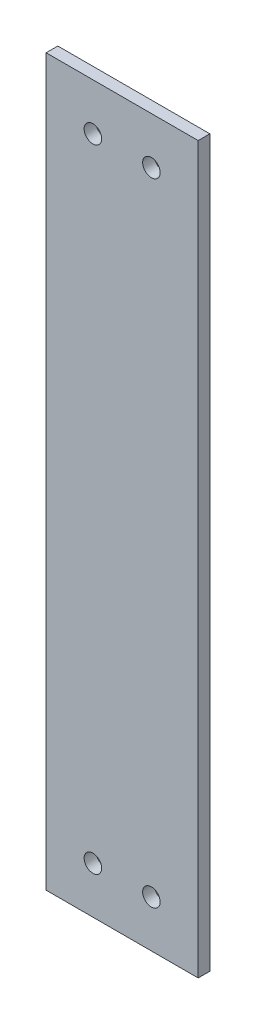
SolidWorks part; units mm, degrees
ref_plane "Спереди" through (0, 0, 0) normal (0, 0, 1) x (1, 0, 0)
ref_plane "Сверху" through (0, 0, 0) normal (0, 1, 0) x (1, 0, 0)
ref_plane "Справа" through (0, 0, 0) normal (1, 0, 0) x (0, 0, -1)
sketch "Эскиз1" plane through (0, 0, 0) normal (0, 0, 1) x (1, 0, 0)
  line L1 (0, 0) -> (26, 0)
  line L2 (0, 0) -> (0, 124)
  line L3 (0, 124) -> (26, 124)
  line L4 (26, 0) -> (26, 124)
  circle A0 centre (8, 8) radius 1.5
  circle A1 centre (18, 8) radius 1.5
  circle A2 centre (18, 116) radius 1.5
  circle A3 centre (8, 116) radius 1.5
  dimension "D3" = 3
  dimension "D2" = 10
  dimension "D4" = 8
  dimension "D5" = 8
  dimension "D8" = 8
  dimension "D9" = 8
  dimension "D10" = 8
  dimension "D11" = 108
  dimension "D7" = 2
  dimension "D6" = 2
extrude "Бобышка-Вытянуть1" add sketch "Эскиз1" along normal blind 2
